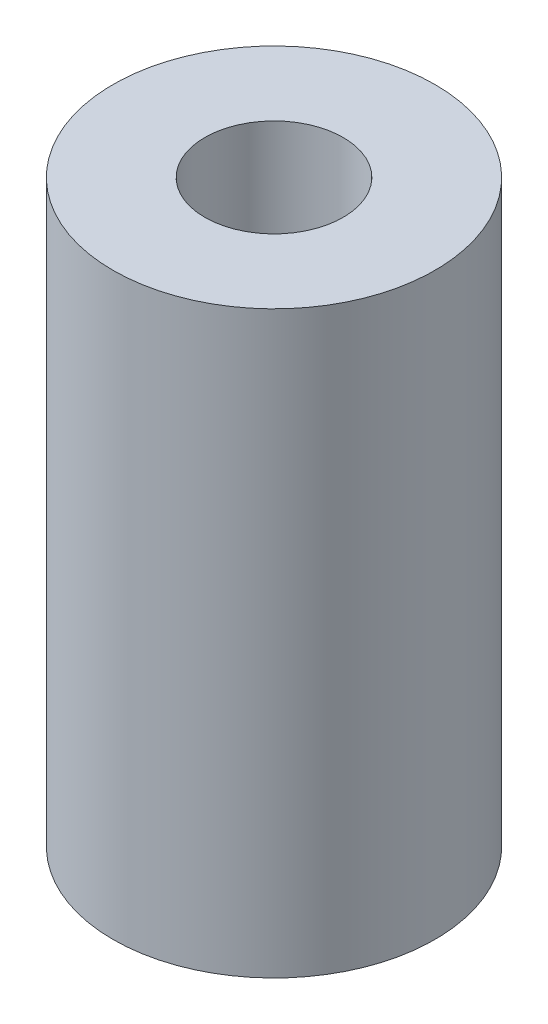
SolidWorks part; units mm, degrees
ref_plane "Спереди" through (0, 0, 0) normal (0, 0, 1) x (1, 0, 0)
ref_plane "Сверху" through (0, 0, 0) normal (0, 1, 0) x (1, 0, 0)
ref_plane "Справа" through (0, 0, 0) normal (1, 0, 0) x (0, 0, -1)
sketch "Эскиз1" plane through (0, 0, 0) normal (0, 1, 0) x (1, 0, 0)
  circle A0 centre (0, 0) radius 5
  circle A1 centre (0, 0) radius 2.15
  dimension "D1" = 4.3
  dimension "D2" = 10
extrude "тело" add sketch "Эскиз1" along normal blind 18
